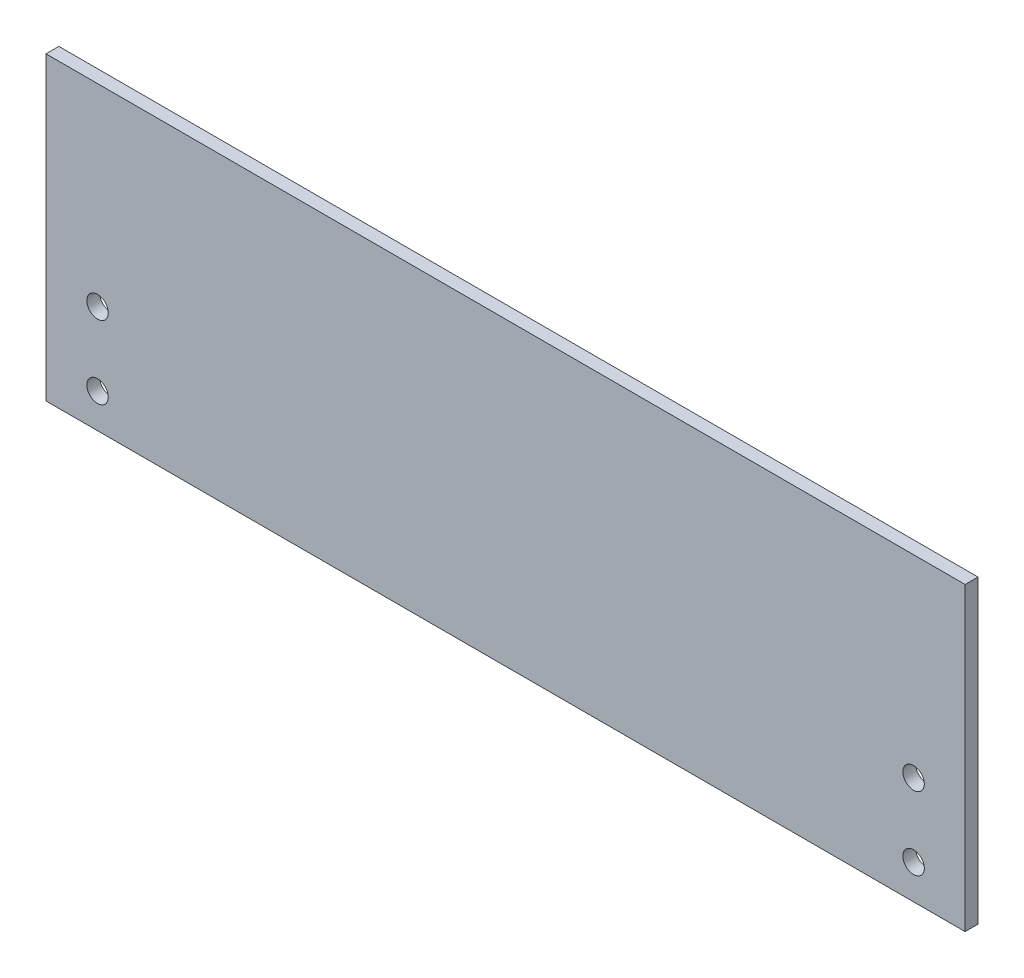
SolidWorks part; units mm, degrees
ref_plane "前视基准面" through (0, 0, 0) normal (0, 0, 1) x (1, 0, 0)
ref_plane "上视基准面" through (0, 0, 0) normal (0, 1, 0) x (1, 0, 0)
ref_plane "右视基准面" through (0, 0, 0) normal (1, 0, 0) x (0, 0, -1)
sketch "草图1" plane through (0, 0, 0) normal (0, 0, 1) x (1, 0, 0)
  line L0 (0, 63.8429) -> (0, -71.477) construction
  line L1 (-107, 35) -> (107, 35)
  line L2 (-107, 35) -> (-107, -35)
  line L3 (-107, -35) -> (107, -35)
  line L4 (107, 35) -> (107, -35)
  line L5 (-107, 35) -> (107, -35) construction
  line L6 (-107, -35) -> (107, 35) construction
  circle A0 centre (-95, -10) radius 2.5
  circle A1 centre (-95, -27) radius 2.5
  circle A2 centre (95, -27) radius 2.5
  circle A3 centre (95, -10) radius 2.5
  point P0 (0, 0)
  point P16 (-95, -10)
  dimension "D3" = 5
  dimension "D4" = 5
  dimension "D1" = 214
  dimension "D2" = 70
  dimension "D5" = 17
  dimension "D6" = 8
  dimension "D7" = 12
extrude "凸台-拉伸1" add sketch "草图1" along normal blind 3
